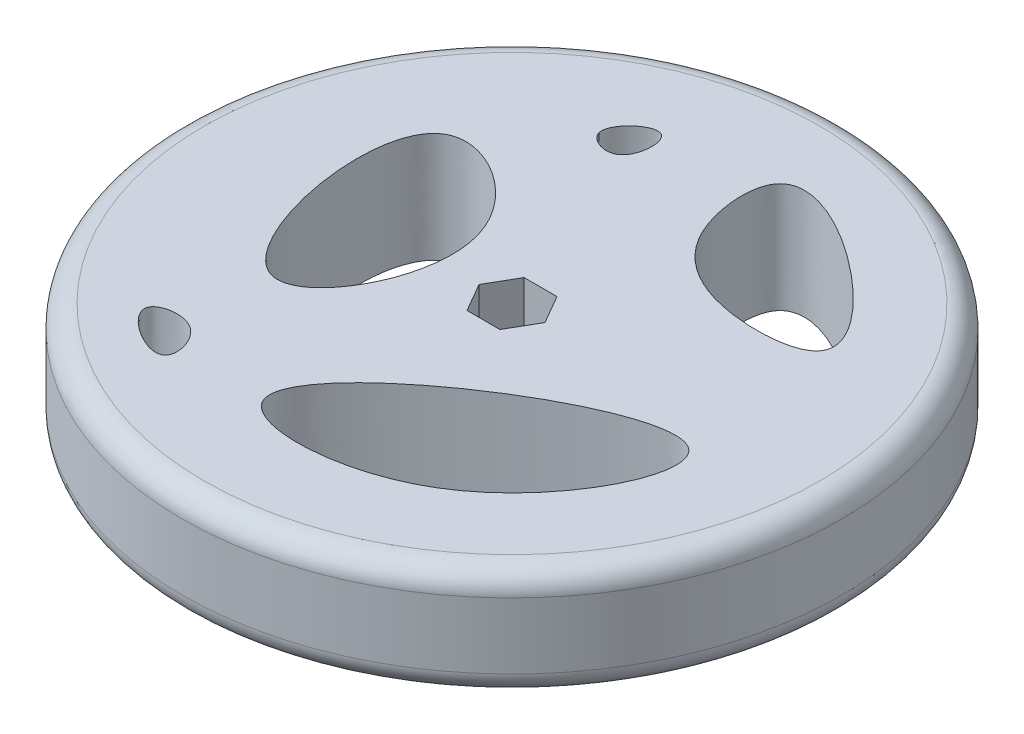
SolidWorks part; units mm, degrees
material "PVC 0.007 Plasticized"
ref_plane "Front Plane" through (0, 0, 0) normal (0, 0, 1) x (1, 0, 0)
ref_plane "Top Plane" through (0, 0, 0) normal (0, 1, 0) x (1, 0, 0)
ref_plane "Right Plane" through (0, 0, 0) normal (1, 0, 0) x (0, 0, -1)
sketch "Sketch1" plane through (0, 0, 0) normal (0, 1, 0) x (1, 0, 0)
  circle A0 centre (0, 0) radius 30
  dimension "D1" = 60
extrude "Boss-Extrude1" add sketch "Sketch1" along normal blind 10
sketch "Sketch2" plane through (0, 10, 0) normal (0, 1, 0) x (1, 0, 0)
  line L1 (1.5, -2.5981) -> (3, 0)
  line L2 (3, 0) -> (1.5, 2.5981)
  line L3 (1.5, 2.5981) -> (-1.5, 2.5981)
  line L4 (-1.5, 2.5981) -> (-3, 0)
  line L5 (-3, 0) -> (-1.5, -2.5981)
  line L6 (-1.5, -2.5981) -> (1.5, -2.5981)
  circle A0 centre (0, 0) radius 2.5981 construction
  dimension "D1" = 6
extrude "Cut-Extrude1" cut sketch "Sketch2" against normal blind 7
fillet "Fillet1" radius 2 2 edges at (0, 0, 30) (0, 10, 30)
sketch "Sketch3" plane through (0, 10, 0) normal (0, 1, 0) x (1, 0, 0)
  spline S0 degree 3 poles (-1.869, 4.5338) (-22.7357, 17.2377) (-15.2475, -19.7861) (-1.869, 4.5338) (-22.7357, 17.2377) (-15.2475, -19.7861) knots -1 -0.565977 -0.250715 0 0.434023 0.749285 1 1.434023 1.749285 2 only from (-16.3077, 10.3441) to (-16.3077, 10.3441)
  spline S1 degree 3 poles (-17.2463, -21.5511) (14.0402, -21.4406) (28.801, 8.4676) (-17.2463, -21.5511) (14.0402, -21.4406) (28.801, 8.4676) knots -1 -0.717102 -0.247808 0 0.282898 0.752192 1 1.282898 1.752192 2 only from (11.0301, -17.9966) to (11.0301, -17.9966)
  spline S2 degree 3 poles (2.0928, 13.2992) (1.4391, 24.8034) (12.8307, 19.2524) (21.3584, 9.1993) (8.3769, 8.4782) (2.0928, 13.2992) (1.4391, 24.8034) (12.8307, 19.2524) knots -0.539614 -0.359153 -0.135143 0 0.242585 0.460386 0.640847 0.864857 1 1.242585 1.460386 1.640847 only from (2.5332, 21.3742) to (2.5332, 21.3742)
  spline S3 degree 3 poles (-5.5141, 22.4742) (-11.3607, 17.374) (-5.9438, 15.33) (-5.5141, 22.4742) (-11.3607, 17.374) (-5.9438, 15.33) knots -1 -0.743866 -0.387891 0 0.256134 0.612109 1 1.256134 1.612109 2 only from (-9.4996, 17.416) to (-9.4996, 17.416)
  spline S4 degree 3 poles (-12.0859, -15.2923) (-19.1296, -16.6932) (-10.2759, -22.4102) (-12.0859, -15.2923) (-19.1296, -16.6932) (-10.2759, -22.4102) knots -1 -0.566164 -0.2774 0 0.433836 0.7226 1 1.433836 1.7226 2 only from (-16.3077, -16.941) to (-16.3077, -16.941)
extrude "Cut-Extrude2" cut sketch "Sketch3" against normal up to surface (10 mm away) up to face at (0, 0, 28)
